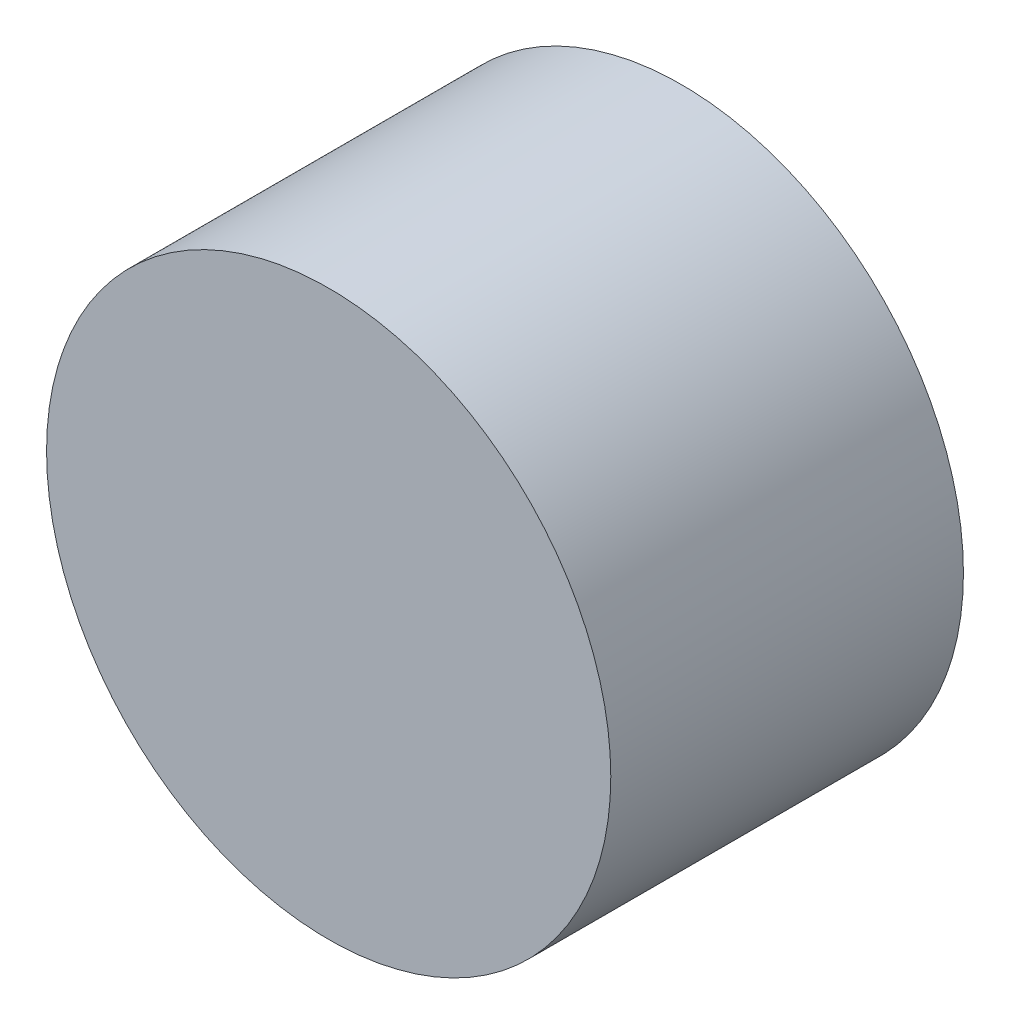
SolidWorks part; units mm, degrees
material "Stainless Steel (ferritic)"
ref_plane "Front Plane" through (0, 0, 0) normal (0, 0, 1) x (1, 0, 0)
ref_plane "Top Plane" through (0, 0, 0) normal (0, 1, 0) x (1, 0, 0)
ref_plane "Right Plane" through (0, 0, 0) normal (1, 0, 0) x (0, 0, -1)
sketch "Sketch1" plane through (0, 0, 0) normal (0, 0, 1) x (1, 0, 0)
  line L0 (0, 15) -> (0, 0) construction
  circle A0 centre (0, 0) radius 20
  circle A1 centre (0, 15) radius 2.5
  circle A2 centre (10.6066, 10.6066) radius 2.5
  circle A3 centre (15, 0) radius 2.5
  circle A4 centre (10.6066, -10.6066) radius 2.5
  circle A5 centre (0, -15) radius 2.5
  circle A6 centre (-10.6066, -10.6066) radius 2.5
  circle A7 centre (-15, 0) radius 2.5
  circle A8 centre (-10.6066, 10.6066) radius 2.5
  circle A9 centre (0, 5) radius 2.5
  circle A10 centre (5, 0) radius 2.5
  circle A11 centre (0, -5) radius 2.5
  circle A12 centre (-5, 0) radius 2.5
  point P21 (0, 0)
  point P31 (0, 0)
  dimension "D1" = 40
  dimension "D3" = 5
  dimension "D4" = 8
  dimension "D5" = 5
  dimension "D2" = 15
  dimension "D6" = 5
  dimension "D7" = 4
extrude "Boss-Extrude1" add sketch "Sketch1" along normal blind 10
sketch "Sketch2" plane through (0, 0, 10) normal (0, 0, 1) x (1, 0, 0)
  circle A0 centre (0, 0) radius 20
extrude "Boss-Extrude2" add sketch "Sketch2" along normal blind 15
